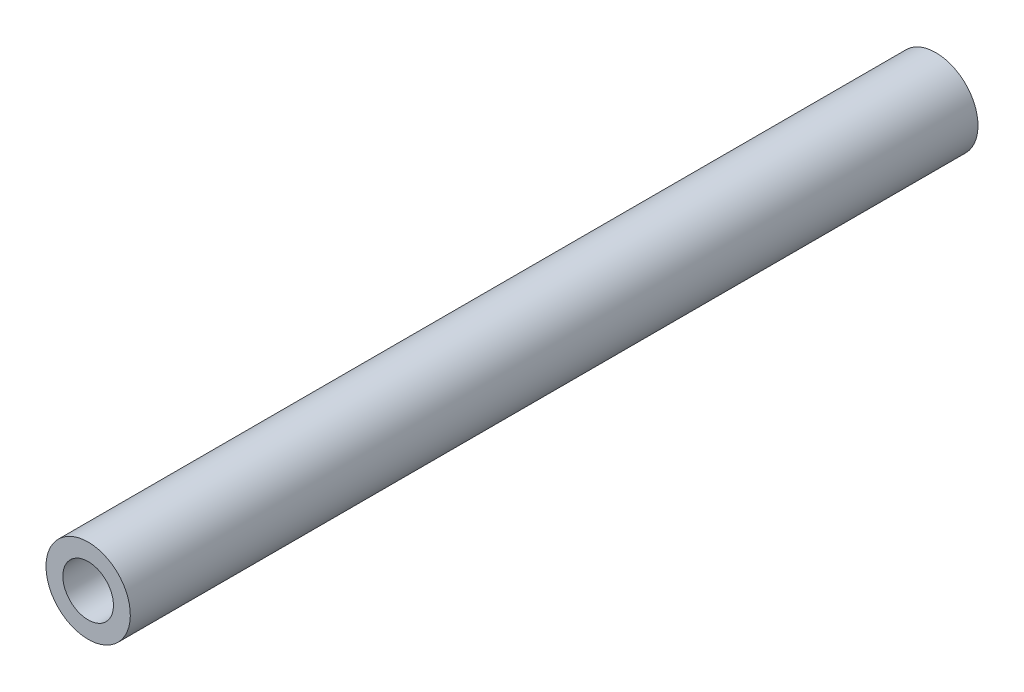
SolidWorks part; units mm, degrees
material "1.0553 (S355J0)"
ref_plane "Front Plane" through (0, 0, 0) normal (0, 0, 1) x (1, 0, 0)
ref_plane "Top Plane" through (0, 0, 0) normal (0, 1, 0) x (1, 0, 0)
ref_plane "Right Plane" through (0, 0, 0) normal (1, 0, 0) x (0, 0, -1)
sketch "Sketch1" plane through (0, 0, 0) normal (1, 0, 0) x (0, 0, -1)
  line L0 (0, 30) -> (0, 50)
  line L1 (0, 50) -> (-1005, 50)
  line L2 (-1005, 50) -> (-1005, 30)
  line L3 (-1005, 30) -> (0, 30)
  line L4 (30.0522, 0) -> (-755.8122, 0) construction
  line L5 (0, 0) -> (0, 30) construction
  dimension "D1" = 60
  dimension "D2" = 100
  dimension "D3" = 1005
revolve "Revolve1" add sketch "Sketch1" angle 360 about L4
